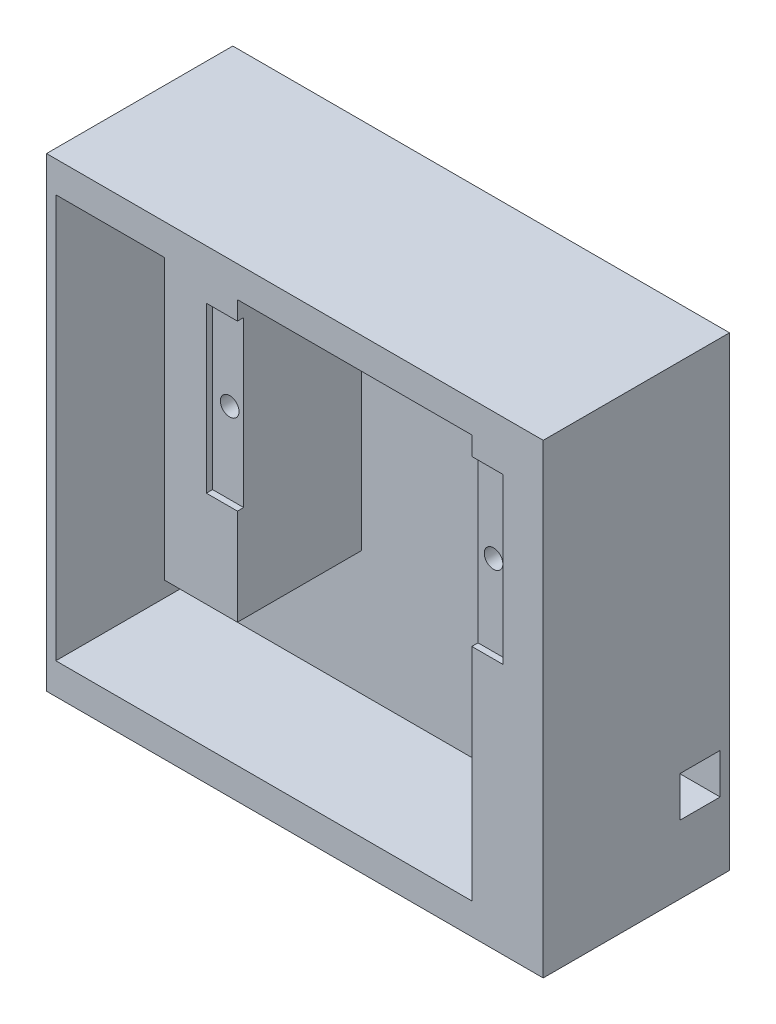
SolidWorks part; units mm, degrees
ref_plane "Front Plane" through (0, 0, 0) normal (0, 0, 1) x (1, 0, 0)
ref_plane "Top Plane" through (0, 0, 0) normal (0, 1, 0) x (1, 0, 0)
ref_plane "Right Plane" through (0, 0, 0) normal (1, 0, 0) x (0, 0, -1)
sketch "Sketch2" plane through (0, 0, 0) normal (0, 0, 1) x (1, 0, 0)
  line L1 (0, 0) -> (-160, 0)
  line L2 (0, 0) -> (0, -150)
  line L3 (0, -150) -> (-160, -150)
  line L4 (-160, 0) -> (-160, -150)
  dimension "D1" = 160
  dimension "D2" = 150
extrude "Boss-Extrude1" add sketch "Sketch2" along normal blind 60
sketch "Sketch3" plane through (0, 0, 60) normal (0, 0, 1) x (1, 0, 0)
  line L0 (0, 0) -> (-160, 0) construction
  line L1 (-98.5, -10) -> (-23, -10)
  line L2 (-98.5, -10) -> (-98.5, -100)
  line L4 (-23, -10) -> (-23, -140)
  line L5 (-157, -140) -> (-23, -140)
  line L6 (-160, -150) -> (0, -150) construction
  line L8 (-160, 0) -> (-160, -150) construction
  line L9 (0, -150) -> (0, 0) construction
  line L10 (-157, -100) -> (-98.5, -100)
  line L11 (-157, -100) -> (-157, -140)
  dimension "D1" = 10
  dimension "D2" = 75.5
  dimension "D3" = 10
  dimension "D4" = 23
  dimension "D5" = 3
  dimension "D7" = 100
extrude "Cut-Extrude1" cut sketch "Sketch3" against normal blind 40
sketch "Sketch4" plane through (0, 0, 60) normal (0, 0, 1) x (1, 0, 0)
  line L1 (0, -150) -> (0, 0) construction
  line L2 (0, 0) -> (-160, 0) construction
  circle A0 centre (-103, -43) radius 3
  circle A1 centre (-18, -43) radius 3
  dimension "D1" = 6
  dimension "D2" = 6
  dimension "D3" = 85
  dimension "D4" = 18
  dimension "D5" = 43
  dimension "D6" = 43
extrude "Cut-Extrude2" cut sketch "Sketch4" against normal blind 40
sketch "Sketch5" plane through (0, 0, 0) normal (1, 0, 0) x (0, 0, -1)
  line L0 (-60, -150) -> (0, -150) construction
  line L1 (-16, -115) -> (-3, -115)
  line L2 (-16, -115) -> (-16, -128)
  line L3 (-16, -128) -> (-3, -128)
  line L4 (-3, -115) -> (-3, -128)
  line L5 (0, -150) -> (0, 0) construction
  point P4 (-9.5, -128)
  dimension "D1" = 22
  dimension "D2" = 13
  dimension "D3" = 13
  dimension "D4" = 3
extrude "Cut-Extrude3" cut sketch "Sketch5" against normal up to surface (23 mm away) up to face at (-23, -75, 40)
sketch "Sketch6" plane through (0, 0, 60) normal (0, 0, 1) x (1, 0, 0)
  line L0 (-98.5, -10) -> (-98.5, -100) construction
  line L1 (-108.5, -16) -> (-98.5, -16)
  line L2 (-108.5, -16) -> (-108.5, -69)
  line L3 (-108.5, -69) -> (-98.5, -69)
  line L4 (-98.5, -16) -> (-98.5, -69)
  line L5 (-23, -140) -> (-23, -10) construction
  line L6 (-23, -16) -> (-13, -16)
  line L7 (-23, -16) -> (-23, -69)
  line L8 (-23, -69) -> (-13, -69)
  line L9 (-13, -16) -> (-13, -69)
  line L10 (0, 0) -> (-160, 0) construction
  point P12 (-103.5, -16)
  dimension "D1" = 53
  dimension "D2" = 53
  dimension "D3" = 16
  dimension "D4" = 16
  dimension "D5" = 10
  dimension "D6" = 10
extrude "Cut-Extrude4" cut sketch "Sketch6" against normal blind 2
sketch "Sketch7" plane through (0, 0, 60) normal (0, 0, 1) x (1, 0, 0)
  line L0 (0, 0) -> (-160, 0) construction
  line L1 (-157, -10) -> (-122, -10)
  line L2 (-157, -10) -> (-157, -140)
  line L3 (-157, -140) -> (-122, -140)
  line L4 (-122, -10) -> (-122, -140)
  line L5 (-160, 0) -> (-160, -150) construction
  line L7 (-160, -150) -> (0, -150) construction
  dimension "D1" = 10
  dimension "D2" = 35
  dimension "D3" = 3
  dimension "D4" = 10
extrude "Cut-Extrude5" cut sketch "Sketch7" against normal blind 40
